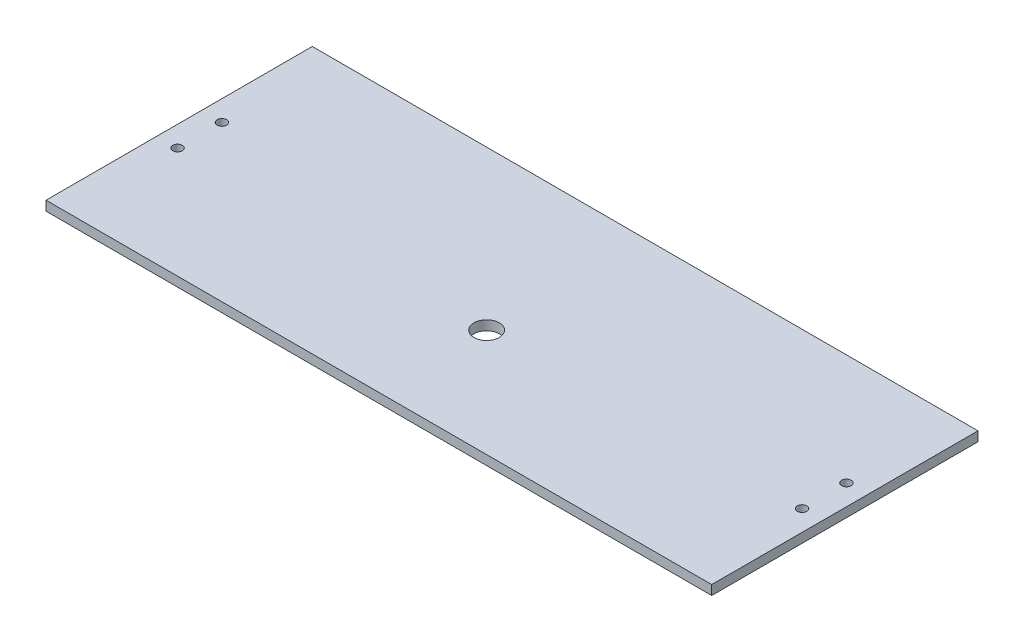
SolidWorks part; units mm, degrees
ref_plane "Alzado" through (0, 0, 0) normal (0, 0, 1) x (1, 0, 0)
ref_plane "Planta" through (0, 0, 0) normal (0, 1, 0) x (1, 0, 0)
ref_plane "Vista lateral" through (0, 0, 0) normal (1, 0, 0) x (0, 0, -1)
sketch "Croquis2" plane through (-13.7319, 703.6284, -26.3243) normal (0, -1, 0) x (-1, 0, 0)
  line L1 (-133.2303, 56.1152) -> (76.7697, 56.1152)
  line L2 (-133.2303, 56.1152) -> (-133.2303, -27.8848)
  line L3 (-133.2303, -27.8848) -> (76.7697, -27.8848)
  line L4 (76.7697, 56.1152) -> (76.7697, -27.8848)
  circle A0 centre (-28.2303, 6.1152) radius 4
  circle A1 centre (-126.7303, 7.1152) radius 1.5
  circle A2 centre (-126.7303, 21.1152) radius 1.5
  circle A3 centre (70.2697, 21.1152) radius 1.5
  circle A4 centre (70.2697, 7.1152) radius 1.5
extrude "Saliente-Extruir1" add sketch "Croquis2" against normal blind 3
